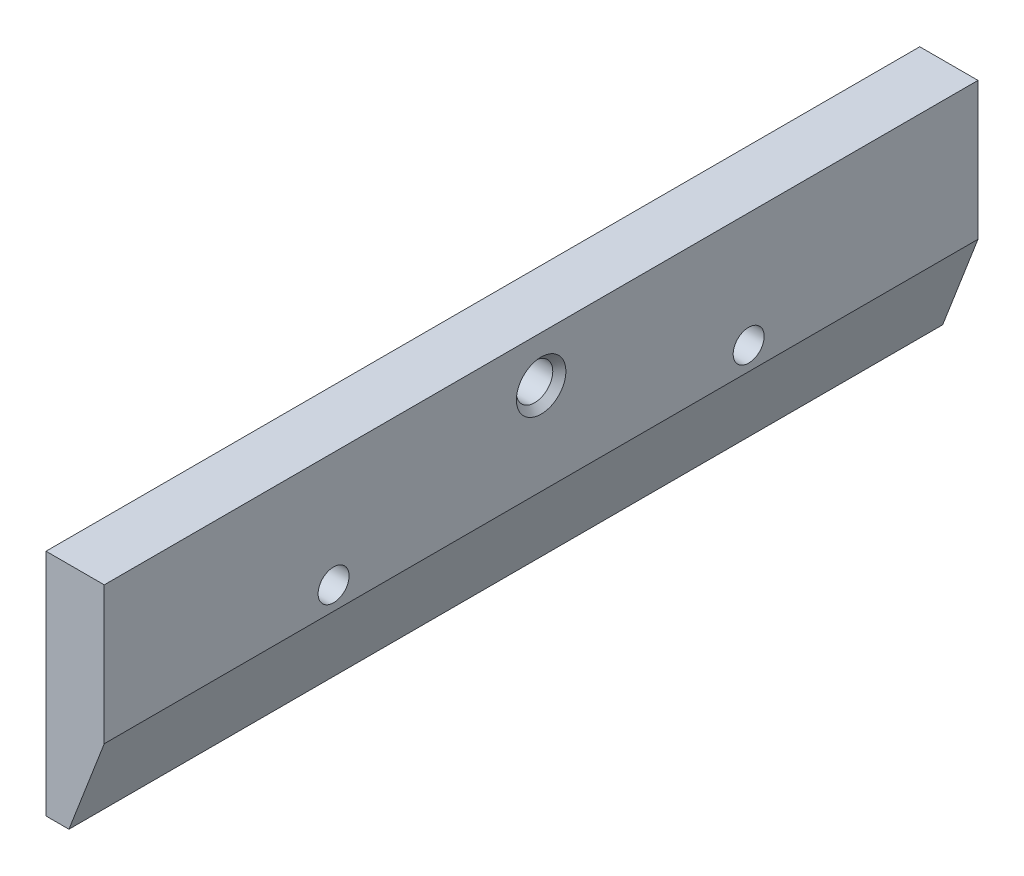
SolidWorks part; units mm, degrees
ref_plane "Alzado" through (0, 0, 0) normal (0, 0, 1) x (1, 0, 0)
ref_plane "Planta" through (0, 0, 0) normal (0, 1, 0) x (1, 0, 0)
ref_plane "Vista lateral" through (0, 0, 0) normal (1, 0, 0) x (0, 0, -1)
sketch "Croquis1" plane through (0, 0, 0) normal (0, 0, 1) x (1, 0, 0)
  line L0 (-1.35, -25) -> (6.35, -5)
  line L1 (6.35, 25) -> (-6.35, 25)
  line L2 (6.35, 25) -> (6.35, -5)
  line L3 (-1.35, -25) -> (-6.35, -25)
  line L4 (-6.35, 25) -> (-6.35, -25)
  point P0 (0, 0)
  point P5 (-6.35, 0)
  point P9 (0, 25)
  dimension "D1" = 50
  dimension "D2" = 12.7
  dimension "D3" = 20
  dimension "D4" = 5
extrude "Saliente-Extruir1" add sketch "Croquis1" along normal mid plane 190.5
hole_wizard "Taladro de margen para 1/41" positions "Croquis3" profile "Croquis5" hole size "1/4" standard "Ansi Inch" end condition through all
sketch "Croquis3" plane through (6.35, 0, 0) normal (1, 0, 0) x (0, 0, -1)
  line L0 (0, 0) -> (0, 50000) construction
  line L2 (-95.25, 0) -> (4.75, 0) construction
  line L3 (-95.25, 25) -> (95.25, 25) construction
  line L4 (-95.25, -5) -> (-95.25, 25) construction
  point P0 (-45.25, 0)
  point P2 (45.25, 0)
  point P20 (-45.25, 0)
  dimension "D1" = 25
  dimension "D2" = 50
sketch "Croquis5" plane through (6.35, 0, 45.25) normal (0, 1, 0) x (0, 0, -1)
  line L0 (0, 0) -> (0, 12.7)
  line L1 (0, 12.7) -> (3.3782, 12.7)
  line L2 (3.3782, 12.7) -> (3.3782, 0)
  line L5 (3.3782, 0) -> (0, 0)
  line L11 (0, -6.35) -> (0, 107.95) construction
  dimension "Diámetro de taladro hasta el siguiente" = 6.7564
  dimension "Profundidad de taladro hasta el siguiente" = 12.7
hole_wizard "Taladro roscado 3/8-161" positions "Croquis6" profile "Croquis7" tap size "3/8-16" standard "Ansi Inch" end condition through all
sketch "Croquis6" plane through (6.35, 0, 0) normal (1, 0, 0) x (0, 0, -1)
  circle A0 centre (0, 15) radius 3.9687 construction
  point P0 (0, 15)
sketch "Croquis7" plane through (6.35, 15, 0) normal (0, 1, 0) x (0, 0, -1)
  line L0 (0, 0) -> (0, 12.7)
  line L1 (0, 12.7) -> (5.3975, 12.7)
  line L2 (3.9687, 11.2712) -> (3.9687, 1.4287)
  line L3 (3.9687, 1.4287) -> (5.3975, 0)
  line L5 (5.3975, 0) -> (0, 0)
  line L6 (-3.9687, 1.4287) -> (-5.3975, 0) construction
  line L7 (5.3975, 12.7) -> (3.9687, 11.2712)
  line L8 (-5.3975, 12.7) -> (-3.9688, 11.2712) construction
  line L11 (0, -6.35) -> (0, 107.95) construction
  dimension "Diámetro de perforador para roscar hasta el siguiente" = 7.9375
  dimension "Profundidad de perforador para roscar hasta el siguiente" = 12.7
  dimension "Diámetro de avellanado cercano" = 10.795
  dimension "Ángulo de avellanado cercano" = 90
  dimension "Diámetro de avellanado lejano" = 10.795
  dimension "Ángulo de avellanado lejano" = 90
cosmetic thread "Rosca de taladro1" parameters "D2"=9.525
